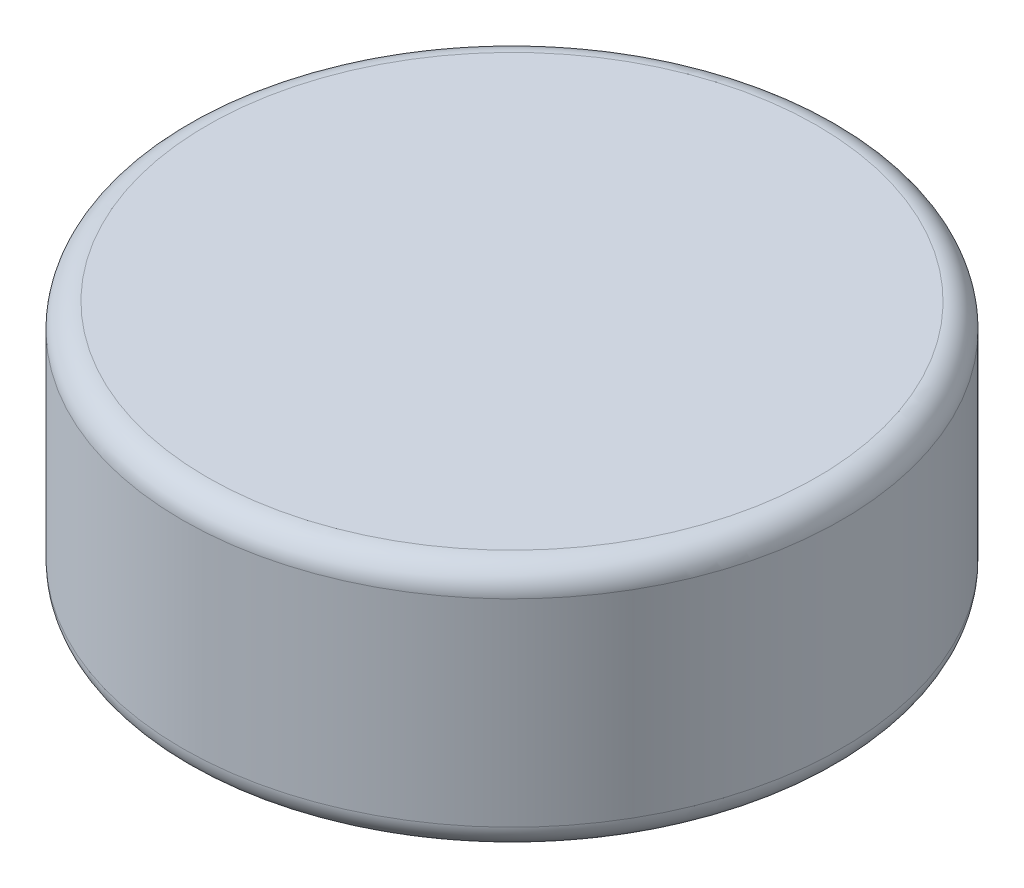
SolidWorks part; units mm, degrees
material "1060 Alloy"
ref_plane "Front Plane" through (0, 0, 0) normal (0, 0, 1) x (1, 0, 0)
ref_plane "Top Plane" through (0, 0, 0) normal (0, 1, 0) x (1, 0, 0)
ref_plane "Right Plane" through (0, 0, 0) normal (1, 0, 0) x (0, 0, -1)
sketch "Sketch1" plane through (0, 0, 0) normal (0, 1, 0) x (1, 0, 0)
  circle A0 centre (0, 0) radius 6.35
  dimension "OD" = 12.7
extrude "Boss-Extrude1" add sketch "Sketch1" along normal mid plane 4.7625
fillet "Fillet1" radius 0.4762 2 edges at (0, -2.3813, 6.35) (0, 2.3813, 6.35)
equation "\"D1@Fillet1\"=\"Thickness@Boss-Extrude1\"/10"
